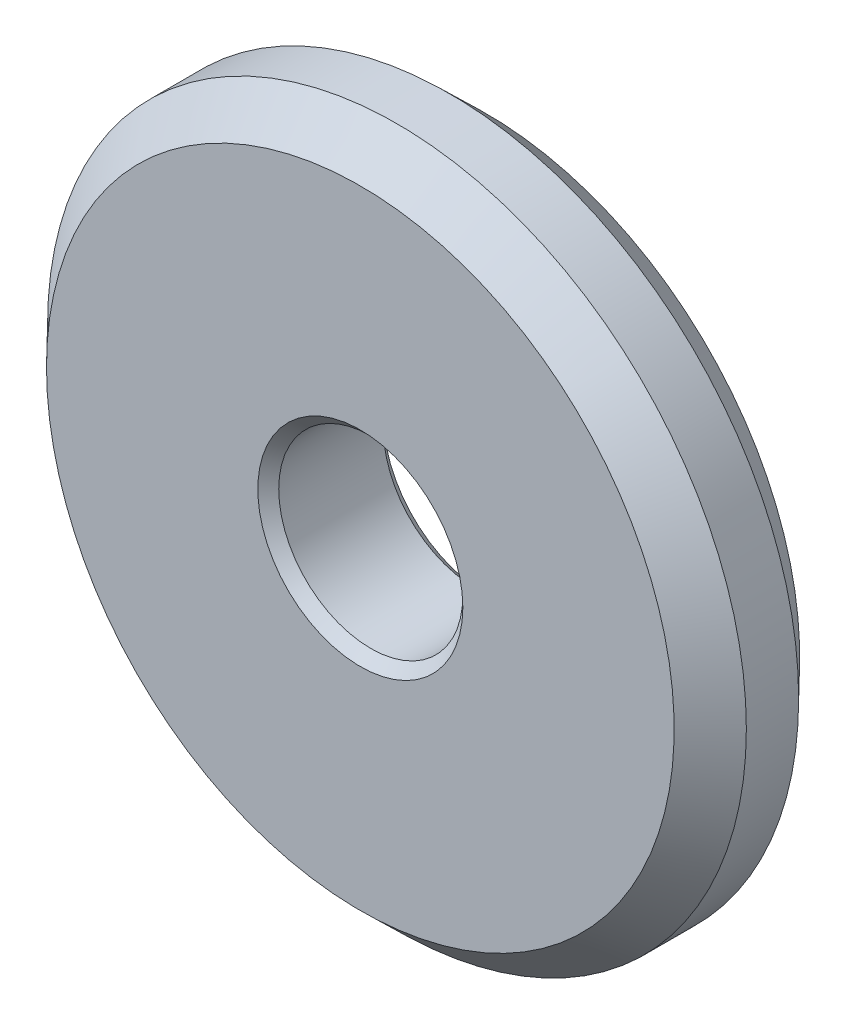
SolidWorks part; units mm, degrees
material "17CrNiMo6"
ref_plane "Front Plane" through (0, 0, 0) normal (0, 0, 1) x (1, 0, 0)
ref_plane "Top Plane" through (0, 0, 0) normal (0, 1, 0) x (1, 0, 0)
ref_plane "Right Plane" through (0, 0, 0) normal (1, 0, 0) x (0, 0, -1)
sketch "Sketch1" plane through (0, 0, 0) normal (1, 0, 0) x (0, 0, -1)
  line L0 (0, 4.4) -> (0, 15)
  line L1 (0, 15) -> (-1.75, 16.7)
  line L2 (-1.75, 16.7) -> (-4.25, 16.7)
  line L3 (-4.25, 16.7) -> (-6, 15)
  line L4 (-6, 15) -> (-6, 4.4)
  line L5 (-6, 4.4) -> (0, 4.4)
  line L6 (0, 0) -> (-6, 0) construction
  point P9 (-3, 16.7)
  point P10 (-3, 4.4)
  dimension "D1" = 6
  dimension "D2" = 8.8
  dimension "D3" = 33.4
  dimension "D4" = 2.5
  dimension "D5" = 30
revolve "Revolve1" add sketch "Sketch1" angle 360 about L6
chamfer "Chamfer1" distance 0.5 angle 45 2 edges at (-4.4, 0, 6) (-4.4, 0, 0)
